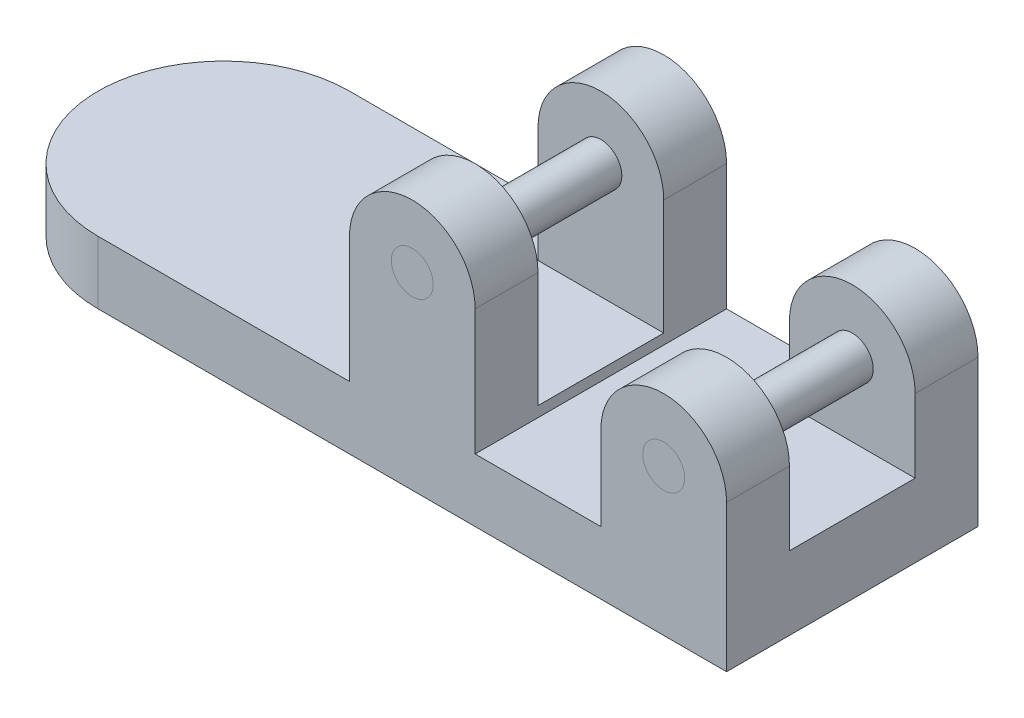
SolidWorks part; units mm, degrees
ref_plane "Front Plane" through (0, 0, 0) normal (0, 0, 1) x (1, 0, 0)
ref_plane "Top Plane" through (0, 0, 0) normal (0, 1, 0) x (1, 0, 0)
ref_plane "Right Plane" through (0, 0, 0) normal (1, 0, 0) x (0, 0, -1)
sketch "Sketch1" plane through (0, 0, 0) normal (0, 1, 0) x (1, 0, 0)
  line L1 (0, 0) -> (150, 0)
  line L3 (0, 60) -> (150, 60)
  line L4 (150, 0) -> (150, 60)
  arc A0 (0, 60) -> (0, 0) centre (0, 30) ccw
  point P5 (0, 30)
  dimension "D1" = 150
  dimension "D2" = 60
extrude "Boss-Extrude1" add sketch "Sketch1" along normal blind 15
sketch "Sketch2" plane through (0, 0, 0) normal (0, 0, 1) x (1, 0, 0)
  line L0 (0, 15) -> (150, 15) construction
  line L1 (75, 15) -> (75, 0) construction
  line L2 (33, 0) -> (-33, 0) construction
  line L3 (60, 15) -> (90, 15)
  line L4 (60, 15) -> (60, 45)
  line L5 (90, 15) -> (90, 45)
  line L6 (120, 15) -> (150, 15)
  line L7 (120, 15) -> (120, 35)
  line L8 (150, 15) -> (150, 35)
  arc A0 (90, 45) -> (60, 45) centre (75, 45) ccw
  arc A1 (150, 35) -> (120, 35) centre (135, 35) ccw
  point P0 (75, 15)
  point P7 (75, 15)
  point P10 (135, 15)
  point P20 (150, 15)
  dimension "D3" = 30
  dimension "D1" = 30
  dimension "D2" = 30
  dimension "D4" = 20
extrude "Boss-Extrude2" add sketch "Sketch2" against normal blind 60
sketch "Sketch3" plane through (150, 0, 0) normal (1, 0, 0) x (0, 0, -1)
  line L0 (0, 17.5) -> (60, 17.5)
  line L1 (0, 35) -> (0, 0) construction
  line L2 (60, 35) -> (60, 0) construction
  line L4 (15, 17.5) -> (45, 17.5)
  line L5 (15, 17.5) -> (15, 69.4182)
  line L6 (15, 69.4182) -> (45, 69.4182)
  line L7 (45, 17.5) -> (45, 69.4182)
  line M7 (60, 35) -> (0, 35)
  dimension "D1" = 15
  dimension "D2" = 30
extrude "Cut-Extrude1" cut sketch "Sketch3" against normal through all contours L0 L7 L5 M7 | L7 L6 L5 M7
sketch "Sketch4" plane through (0, 0, 0) normal (0, 0, 1) x (1, 0, 0)
  line L0 (60, 45) -> (90, 45) construction
  line L1 (120, 35) -> (150, 35) construction
  circle A0 centre (75, 45) radius 5
  circle A1 centre (135, 35) radius 5
extrude "Boss-Extrude3" add sketch "Sketch4" along normal through all and the other way through all contours A1 | A0
